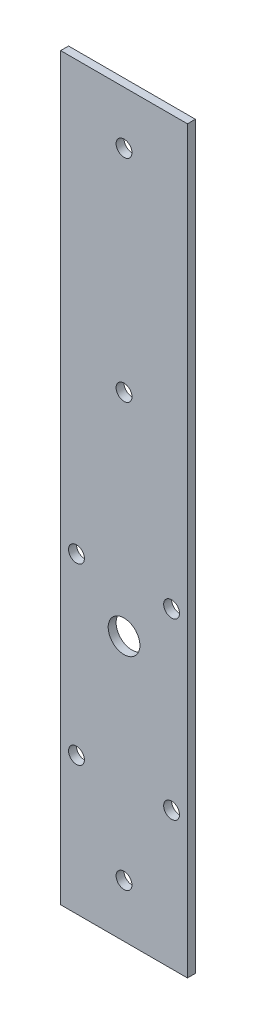
SolidWorks part; units mm, degrees
ref_plane "前视基准面" through (0, 0, 0) normal (0, 0, 1) x (1, 0, 0)
ref_plane "上视基准面" through (0, 0, 0) normal (0, 1, 0) x (1, 0, 0)
ref_plane "右视基准面" through (0, 0, 0) normal (1, 0, 0) x (0, 0, -1)
sketch "草图1" plane through (0, 0, 0) normal (0, 0, 1) x (1, 0, 0)
  line L1 (12, 70) -> (-12, 70)
  line L3 (12, -70) -> (-12, -70)
  line L4 (-12, 70) -> (-12, -70)
  line L5 (0, -70) -> (0, 70) construction
  line L6 (7.5, 0) -> (-12, 0) construction
  line L11 (12, 70) -> (12, -70)
  line L13 (9, -44) -> (-9, -44) construction
  line L14 (9, -44) -> (9, -11) construction
  line L15 (9, -11) -> (-9, -11) construction
  line L16 (-9, -44) -> (-9, -11) construction
  line L17 (0, -11) -> (0, -44) construction
  line L18 (9, -27.5) -> (-9, -27.5) construction
  circle A0 centre (0, 20) radius 1.5
  circle A2 centre (0, -60) radius 1.5
  circle A3 centre (0, 60) radius 1.5
  circle A4 centre (-9, -11) radius 1.5
  circle A5 centre (9, -11) radius 1.5
  circle A6 centre (9, -44) radius 1.5
  circle A7 centre (-9, -44) radius 1.5
  circle A8 centre (0, -20) radius 3
  point P0 (0, 0)
  point P12 (0, -27.5)
  dimension "D3" = 3
  dimension "D5" = 40
  dimension "D6" = 3
  dimension "D1" = 10
  dimension "D4" = 9
  dimension "D10" = 40
  dimension "D7" = 40
  dimension "D2" = 24
  dimension "D8" = 18
  dimension "D9" = 33
extrude "凸台-拉伸1" add sketch "草图1" along normal blind 1.5
sketch "草图4" plane through (0, 0, 1.5) normal (0, 0, 1) x (1, 0, 0)
  line L0 (0.295, -14.0445) -> (0.295, -13.5445)
  line L9 (-0.295, -14.0445) -> (-0.295, -13.5445)
  line L12 (-0.295, -13.5445) -> (0.295, -13.5445)
  line L14 (0, -15) -> (0, -13.5445) construction
  line L15 (-0.0315, -15) -> (0, -15) construction
  arc A1 (-0.295, -14.0445) -> (0.295, -14.0445) centre (0, -15) ccw
  dimension "D2" = 0.5
  dimension "D1" = 0.59
